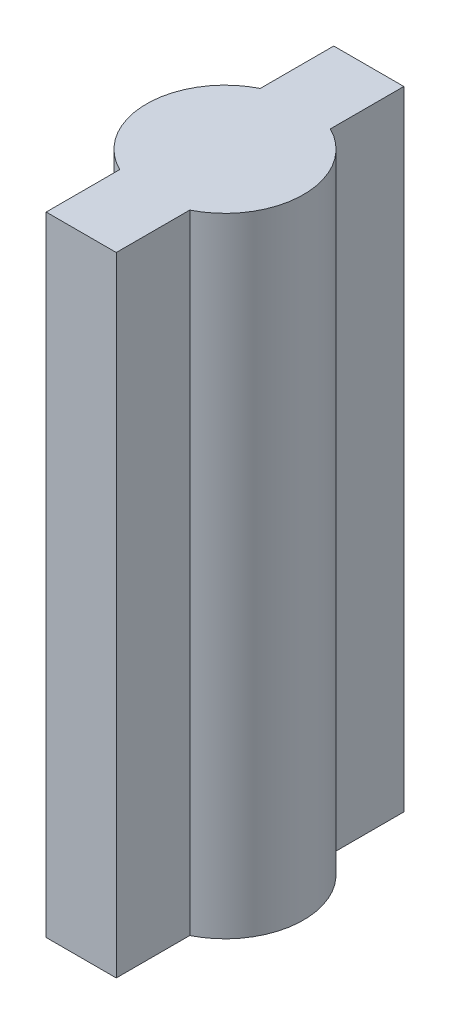
SolidWorks part; units mm, degrees
ref_plane "Front" through (0, 0, 0) normal (0, 0, 1) x (1, 0, 0)
ref_plane "Top" through (0, 0, 0) normal (0, 1, 0) x (1, 0, 0)
ref_plane "Right" through (0, 0, 0) normal (1, 0, 0) x (0, 0, -1)
sketch "Sketch1" plane through (0, 0, 0) normal (0, 1, 0) x (1, 0, 0)
  line L1 (-0.725, 2.975) -> (0.725, 2.975)
  line L2 (-0.725, 2.975) -> (-0.725, -2.975)
  line L3 (-0.725, -2.975) -> (0.725, -2.975)
  line L4 (0.725, 2.975) -> (0.725, -2.975)
  line L5 (-0.725, 2.975) -> (0.725, -2.975) construction
  line L6 (-0.725, -2.975) -> (0.725, 2.975) construction
  circle A0 centre (0, 0) radius 1.625
  dimension "D3" = 3.25
  dimension "D1" = 5.95
  dimension "D2" = 1.45
extrude "Boss-Extrude1" add sketch "Sketch1" along normal mid plane 13 contours L4 A0 | L4 A0 L2 | L2 A0 | A0 L4 L1 L2 | A0 L2 L3 L4
